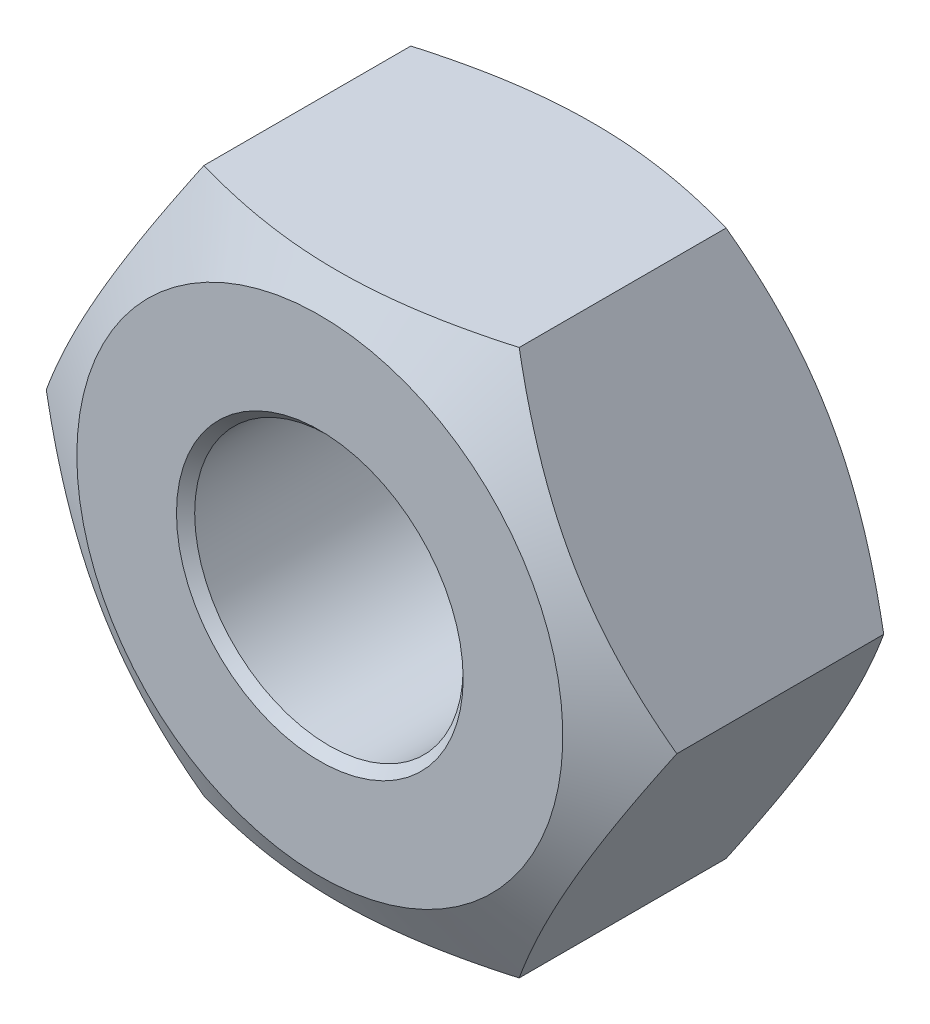
SolidWorks part; units mm, degrees
ref_plane "Front" through (0, 0, 0) normal (0, 0, 1) x (1, 0, 0)
ref_plane "Top" through (0, 0, 0) normal (0, 1, 0) x (1, 0, 0)
ref_plane "Right" through (0, 0, 0) normal (1, 0, 0) x (0, 0, -1)
other "Configuration Table"
sketch "Sketch1" plane through (0, 0, 0) normal (0, 0, 1) x (1, 0, 0)
  line L1 (2.8868, -5) -> (5.7735, 0)
  line L2 (5.7735, 0) -> (2.8868, 5)
  line L3 (2.8868, 5) -> (-2.8868, 5)
  line L4 (-2.8868, 5) -> (-5.7735, 0)
  line L5 (-5.7735, 0) -> (-2.8868, -5)
  line L6 (-2.8868, -5) -> (2.8868, -5)
  circle A0 centre (0, 0) radius 5 construction
  circle A1 centre (0, 0) radius 2.4585
  dimension "D1" = 4.917
  dimension "s" = 10
extrude "BaseNut" add sketch "Sketch1" against normal blind 5
cosmetic thread "ThreadCosmetic1" [suppressed] parameters "D2"=6
sketch "Sketch2" plane through (15.0481, 0, -16.7061) normal (0, 1, 0) x (0, 0, -1)
  line L0 (-23.7227, 15.0481) -> (22.0646, 15.0481) construction
  line L2 (-11.7061, 20.8216) -> (-11.7061, 17.9349) construction
  line L4 (-11.7061, 20.8216) -> (-16.7061, 20.8216) construction
  line L8 (-12.1527, 20.8216) -> (-11.7061, 20.0481)
  line L9 (-11.7061, 20.8216) -> (-12.1527, 20.8216)
  line L10 (-11.7061, 20.0481) -> (-11.7061, 20.8216)
  dimension "D1" = 30
  dimension "s1" = 10
revolve "Chamfer1" cut sketch "Sketch2" angle 360 about L0
sketch "Sketch6" plane through (-9.1975, 0, -10.2525) normal (0, 1, 0) x (0, 0, 1)
  line L0 (23.3574, 9.1975) -> (-22.3023, 9.1975) construction
  line L2 (5.2525, 11.656) -> (5.2525, 12.5725)
  line L4 (5.2525, 12.5725) -> (5.7817, 11.656)
  line L6 (5.7817, 11.656) -> (5.2525, 11.656)
  dimension "da" = 6.75
  dimension "D2" = 60
revolve "EndChamfer1" cut sketch "Sketch6" angle 360 about L0
sketch "Sketch5" plane through (-14.793, 0, -16.9612) normal (0, 1, 0) x (0, 0, 1)
  line L0 (-22.5748, 14.793) -> (24.743, 14.793) construction
  line L2 (16.9612, 19.243) -> (16.9612, 20.5665)
  line L4 (16.9612, 20.5665) -> (16.1971, 20.5665)
  line L6 (16.1971, 20.5665) -> (16.9612, 19.243)
  dimension "dw1" = 8.9
  dimension "D2" = 30
revolve "Chamfer2" cut sketch "Sketch5" angle 360 about L0
sketch "Sketch3" plane through (-20.9491, 1.8856, 0) normal (0, 0, 1) x (1, 0, 0)
  circle A1 centre (20.9491, -1.8856) radius 2.4585 construction
  circle A2 centre (20.9491, -1.8856) radius 4.45
  circle A3 centre (20.9491, -1.8856) radius 2.4585
  dimension "dw" = 8.9
extrude "Extrude1" [suppressed] add sketch "Sketch3" along normal blind 0.5
chamfer "EndChamfer3" [suppressed] distance 0.1667 angle 45
chamfer "EndChamfer2" distance 0.1667 angle 45 1 edges at (2.4585, 0, 0)
sketch "Sketch7" plane through (0, 0, 0) normal (0, 1, 0) x (1, 0, 0)
  line L0 (0, 48.6183) -> (0, -13.0076) construction
  line L1 (1.917, 4.7416) -> (2.4585, 4.7416)
  line L2 (2.4585, 4.7416) -> (2.9275, 4.4709)
  line L3 (2.9275, 4.4709) -> (2.4585, 4.2001)
  line L4 (2.4585, 4.2001) -> (1.917, 4.2001)
  line L5 (1.917, 4.2001) -> (1.917, 4.7416)
  line L6 (2.4585, 4.4709) -> (-2.4585, 4.4709) construction
  dimension "D1" = 0.5415
  dimension "D2" = 4.917
revolve "Cut-Revolve10" [suppressed] cut sketch "Sketch7" angle 360 about L0
pattern_linear "LPattern10" [suppressed] count 7 spacing 0.6498 along (0, 0, -1)
equation "\"D1@EndChamfer3\" = \"m@BaseNut\" / 30"
equation "\"D1@EndChamfer2\" = \"m@BaseNut\" / 30"
equation "\"s1@Sketch2\" = \"s@Sketch1\""
equation "\"D2@Sketch7\" = \"D1@Sketch1\""
equation "\"D1@Sketch7\" = (  \"D2@ThreadCosmetic1\" - \"D1@Sketch1\" )  / 2"
equation "\"D3@LPattern10\" = \"D1@Sketch7\" * 1.2"
equation "\"D1@LPattern10\" = \"m@BaseNut\" / \"D3@LPattern10\" - 1"
